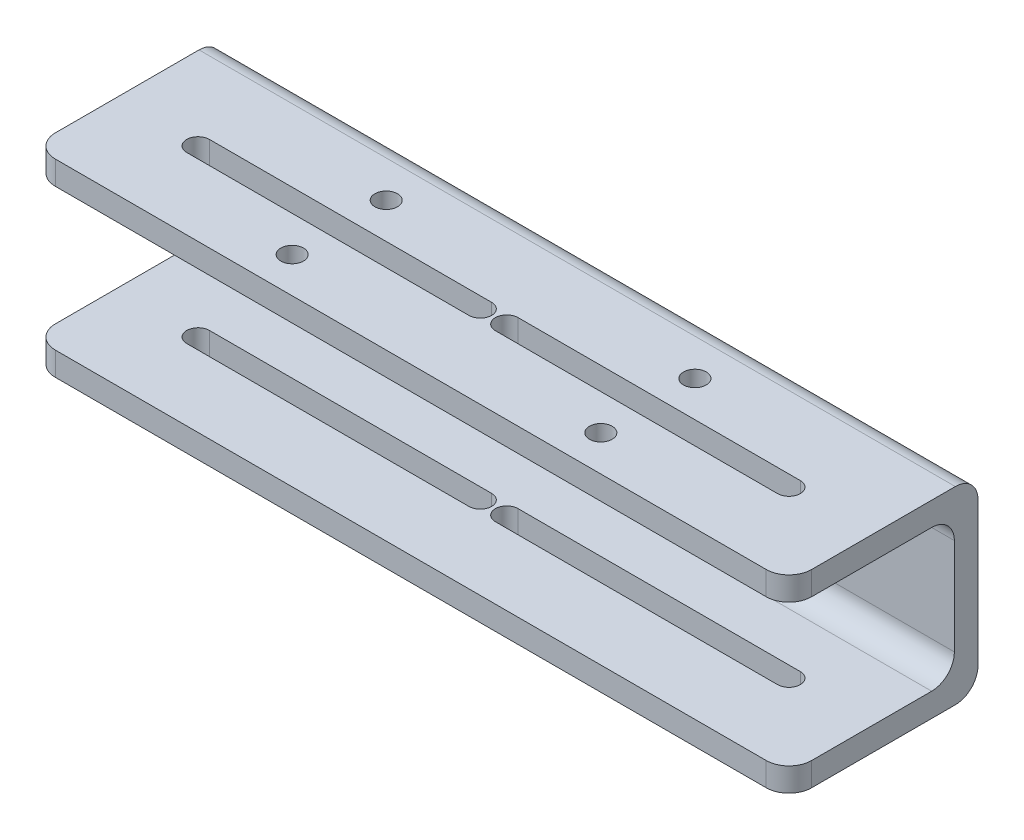
SolidWorks part; units mm, degrees
material "6063-T6"
ref_plane "Front Plane" through (0, 0, 0) normal (0, 0, 1) x (1, 0, 0)
ref_plane "Top Plane" through (0, 0, 0) normal (0, 1, 0) x (1, 0, 0)
ref_plane "Right Plane" through (0, 0, 0) normal (1, 0, 0) x (0, 0, -1)
ref_plane "Plane1" through (0, 25.4, 0) normal (0, 1, 0) x (1, 0, 0)
sketch "Sketch2" plane through (0, 25.4, 0) normal (0, 1, 0) x (1, 0, 0)
  line L1 (-24.8019, 13.1573) -> (76.7981, 13.1573)
  line L2 (-24.8019, 13.1573) -> (-24.8019, -12.2427)
  line L3 (-24.8019, -12.2427) -> (76.7981, -12.2427)
  line L4 (76.7981, 13.1573) -> (76.7981, -12.2427)
  dimension "D1" = 25.4
  dimension "D2" = 101.6
extrude "Boss-Extrude1" add sketch "Sketch2" along normal blind 25.4
sketch "Sketch3" plane through (0, 0, 12.2427) normal (0, 0, 1) x (1, 0, 0)
  line L0 (-24.8019, 50.8) -> (-24.8019, 25.4) construction
  line L1 (-24.8019, 47.625) -> (76.7981, 47.625)
  line L2 (-24.8019, 47.625) -> (-24.8019, 28.575)
  line L3 (-24.8019, 28.575) -> (76.7981, 28.575)
  line L4 (76.7981, 47.625) -> (76.7981, 28.575)
  line L5 (76.7981, 50.8) -> (76.7981, 25.4) construction
  line L6 (-24.8019, 50.8) -> (76.7981, 50.8) construction
  line L7 (13.97, 25.4) -> (-13.97, 25.4) construction
  dimension "D1" = 3.175
  dimension "D2" = 3.175
extrude "Cut-Extrude1" cut sketch "Sketch3" against normal blind 22.225
sketch "Sketch4" plane through (0, 50.8, 0) normal (0, 1, 0) x (1, 0, 0)
  line L0 (-24.8019, 13.1573) -> (-24.8019, -12.2427) construction
  line L1 (-24.8019, -12.2427) -> (76.7981, -12.2427) construction
  line L2 (-13.6894, 0.3938) -> (24.2201, 0.3938)
  line L3 (-13.6894, -2.6542) -> (24.2201, -2.6542)
  arc A0 (-13.6894, 0.3938) -> (-13.6894, -2.6542) centre (-13.6894, -1.1302) ccw
  arc A1 (24.2201, -2.6542) -> (24.2201, 0.3938) centre (24.2201, -1.1302) ccw
  dimension "D1" = 3.048
  dimension "D2" = 11.1125
  dimension "D3" = 11.1125
  dimension "D4" = 3.048
  dimension "D5" = 11.1125
  dimension "D6" = 49.022
extrude "Cut-Extrude2" cut sketch "Sketch4" against normal blind 25.4
sketch "Sketch5" plane through (0, 50.8, 0) normal (0, 1, 0) x (1, 0, 0)
  line L0 (76.7981, -12.2427) -> (76.7981, 13.1573) construction
  line L1 (-24.8019, -12.2427) -> (76.7981, -12.2427) construction
  line L2 (27.7761, 0.3938) -> (65.6856, 0.3938)
  line L3 (27.7761, -2.6542) -> (65.6856, -2.6542)
  arc A0 (27.7761, 0.3938) -> (27.7761, -2.6542) centre (27.7761, -1.1302) ccw
  arc A1 (65.6856, -2.6542) -> (65.6856, 0.3938) centre (65.6856, -1.1302) ccw
  dimension "D1" = 3.048
  dimension "D2" = 11.1125
  dimension "D3" = 11.1125
  dimension "D4" = 3.048
  dimension "D5" = 11.1125
  dimension "D6" = 49.022
extrude "Cut-Extrude3" cut sketch "Sketch5" against normal blind 25.4
sketch "Sketch6" plane through (0, 50.8, 0) normal (0, 1, 0) x (1, 0, 0)
  line L0 (-13.6894, -2.6542) -> (24.2201, -2.6542) construction
  line L1 (24.2201, 0.3938) -> (-13.6894, 0.3938) construction
  line L2 (65.6856, 0.3938) -> (27.7761, 0.3938) construction
  line L3 (27.7761, -2.6542) -> (65.6856, -2.6542) construction
  circle A0 centre (5.2653, -7.4484) radius 1.524
  circle A1 centre (5.2653, 5.1881) radius 1.524
  circle A2 centre (46.7308, 5.1881) radius 1.524
  circle A3 centre (46.7308, -7.4484) radius 1.524
  point P8 (5.2653, -2.6542)
  point P11 (5.2653, 0.3938)
  point P14 (46.7308, 0.3938)
  dimension "D1" = 3.048
  dimension "D2" = 3.048
  dimension "D3" = 3.048
  dimension "D4" = 3.048
  dimension "D7" = 4.7942
  dimension "D8" = 4.7942
  dimension "D5" = 4.7942
  dimension "D6" = 4.7942
extrude "Cut-Extrude4" cut sketch "Sketch6" against normal blind 3.175
sketch "Sketch7" plane through (0, 0, -13.1573) normal (0, 0, -1) x (-1, 0, 0)
  line L0 (13.97, 25.4) -> (-13.97, 25.4) construction
  line L1 (-76.7981, 50.8) -> (-76.7981, 25.4) construction
  circle A0 centre (-56.4781, 38.1) radius 1.524
  circle A1 centre (-36.1581, 38.1) radius 1.524
  circle A2 centre (-15.8381, 38.1) radius 1.524
  circle A3 centre (4.4819, 38.1) radius 1.524
  dimension "D1" = 3.048
  dimension "D2" = 3.048
  dimension "D3" = 3.048
  dimension "D4" = 3.048
  dimension "D5" = 12.7
  dimension "D6" = 12.7
  dimension "D7" = 12.7
  dimension "D8" = 12.7
  dimension "D9" = 20.32
  dimension "D10" = 20.32
  dimension "D11" = 20.32
  dimension "D12" = 20.32
extrude "Cut-Extrude5" cut sketch "Sketch7" against normal blind 3.175
fillet "Fillet1" radius 3.048 2 edges at (25.9981, 47.625, -9.9823) (25.9981, 28.575, -9.9823)
fillet "Fillet2" radius 3.048 2 edges at (25.9981, 25.4, -13.1573) (25.9981, 50.8, -13.1573)
fillet "Fillet3" radius 3.048 4 edges at (76.7981, 26.9875, 12.2427) (76.7981, 49.2125, 12.2427) (-24.8019, 26.9875, 12.2427) (-24.8019, 49.2125, 12.2427)
